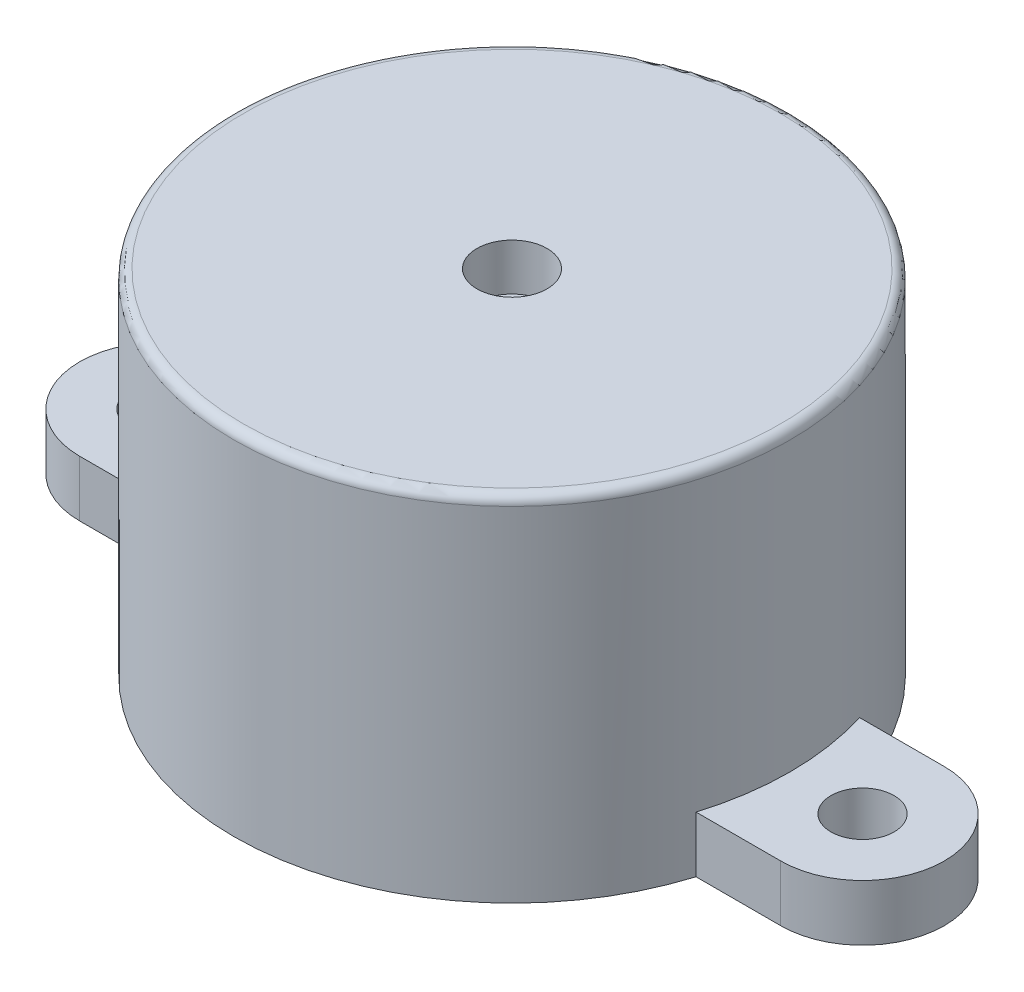
SolidWorks part; units mm, degrees
ref_plane "Front Plane" through (0, 0, 0) normal (0, 0, 1) x (1, 0, 0)
ref_plane "Top Plane" through (0, 0, 0) normal (0, 1, 0) x (1, 0, 0)
ref_plane "Right Plane" through (0, 0, 0) normal (1, 0, 0) x (0, 0, -1)
sketch "Sketch2" plane through (0, 0, 0) normal (0, 0, 1) x (1, 0, 0)
  line L0 (0, 0) -> (0, 23.8886) construction
  line L1 (0, 0) -> (15.113, 0)
  line L2 (15.113, 0) -> (15.113, 19.177)
  line L3 (15.113, 19.177) -> (1.905, 19.177)
  line L4 (1.905, 19.177) -> (1.905, 16.637)
  line L5 (1.905, 16.637) -> (0, 16.637)
  line L6 (0, 16.637) -> (0, 0)
  dimension "D1" = 30.226
  dimension "D2" = 19.177
  dimension "D3" = 3.81
  dimension "D4" = 2.54
revolve "Revolve1" add sketch "Sketch2" angle 360 about L0
sketch "Sketch3" plane through (0, 0, 0) normal (0, -1, 0) x (1, 0, 0)
  line L0 (0, 0) -> (0, 21.1358) construction
  line L1 (0.3888, 0) -> (38.6804, 0) construction
  line L2 (-19.05, 4.445) -> (19.05, 4.445)
  line L3 (-19.05, -4.445) -> (19.05, -4.445)
  circle A0 centre (19.05, 0) radius 1.7145
  arc A1 (19.05, -4.445) -> (19.05, 4.445) centre (19.05, 0) ccw
  arc A2 (-19.05, -4.445) -> (-19.05, 4.445) centre (-19.05, 0) cw
  circle A3 centre (-19.05, 0) radius 1.7145
  dimension "D1" = 3.429
  dimension "D2" = 8.89
  dimension "D3" = 38.1
extrude "Boss-Extrude1" add sketch "Sketch3" against normal blind 3.048
fillet "Fillet2" radius 0.508 1 edges at (0, 19.177, -15.113)
